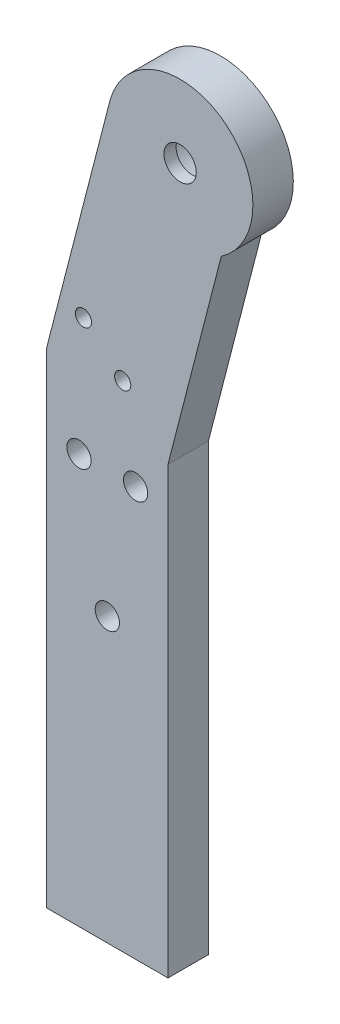
SolidWorks part; units mm, degrees
ref_plane "Front Plane" through (0, 0, 0) normal (0, 0, 1) x (1, 0, 0)
ref_plane "Top Plane" through (0, 0, 0) normal (0, 1, 0) x (1, 0, 0)
ref_plane "Right Plane" through (0, 0, 0) normal (1, 0, 0) x (0, 0, -1)
sketch "Sketch1" plane through (0, 0, 0) normal (0, 0, 1) x (1, 0, 0)
  line L0 (8.6625, 63.8923) -> (8.6625, 8.8923)
  line L1 (-6.3375, 8.8923) -> (-6.3375, 68.8923)
  line L2 (-6.3375, 68.8923) -> (1.556, 99.5244)
  line L3 (8.6625, 8.8923) -> (-6.3375, 8.8923)
  line L4 (8.6625, 63.8923) -> (15.2538, 89.4707)
  line L5 (1.1625, 8.8923) -> (1.1625, 43.8923) construction
  arc A0 (1.556, 99.5244) -> (15.2538, 89.4707) centre (10.1625, 96.8923) cw
  circle A1 centre (10.1625, 96.8923) radius 6 construction
  circle A2 centre (10.1625, 96.8923) radius 2
  circle A3 centre (1.1625, 43.8923) radius 1.5
  point P8 (1.1625, 8.8923)
  dimension "D1" = 9
  dimension "D2" = 12
  dimension "D7" = 4
  dimension "D8" = 3
  dimension "D3" = 60
  dimension "D4" = 88
  dimension "D5" = 9
  dimension "D6" = 5
  dimension "D9" = 35
extrude "Boss-Extrude1" add sketch "Sketch1" along normal blind 5
sketch "Sketch3" plane through (0, 0, 0) normal (0, 0, -1) x (-1, 0, 0)
  circle A0 centre (-10.1625, 96.8923) radius 4.5
  dimension "D1" = 9
extrude "Cut-Extrude1" cut sketch "Sketch3" against normal blind 3.5
sketch "Sketch7" plane through (0, 0, 0) normal (0, 0, -1) x (-1, 0, 0)
  line L1 (-10.312, 70.2932) -> (2.9413, 82.0718) construction
  line L2 (-1.556, 99.5244) -> (6.3375, 68.8923) construction
  line L3 (4.3438, 76.629) -> (-8.9094, 64.8504) construction
  line L4 (2.9413, 82.0718) -> (6.3375, 68.8923) construction
  line L5 (6.3375, 68.8923) -> (6.3375, 59.1324) construction
  line L6 (6.3375, 68.8923) -> (6.3375, 8.8923) construction
  line L7 (6.3375, 59.1324) -> (-8.6625, 59.1324) construction
  line L8 (-8.6625, 8.8923) -> (-8.6625, 63.8923) construction
  line L9 (-8.6625, 59.1324) -> (-8.6625, 63.8923) construction
  line L11 (-8.6625, 63.8923) -> (-15.2538, 89.4707) construction
  line L12 (-8.6625, 63.8923) -> (-10.312, 70.2932)
  circle A0 centre (1.7949, 74.3637) radius 1
  circle A1 centre (-3.0636, 70.0458) radius 1
  dimension "D2" = 6.61
  dimension "D3" = 5
  dimension "D5" = 3.41
  dimension "D6" = 2
  dimension "D4" = 6.5
  dimension "D1" = 13.61
extrude "Cut-Extrude3" cut sketch "Sketch7" against normal blind 10 contours A1 | A0
sketch "Sketch10" plane through (0, 0, 0) normal (0, 0, -1) x (-1, 0, 0)
  circle A0 centre (2.3375, 59.5123) radius 1.5
  circle A1 centre (-4.6625, 59.5123) radius 1.5
  point P6 (0, 0)
  point P7 (0, 0)
extrude "Cut-Extrude4" cut sketch "Sketch10" against normal through all
